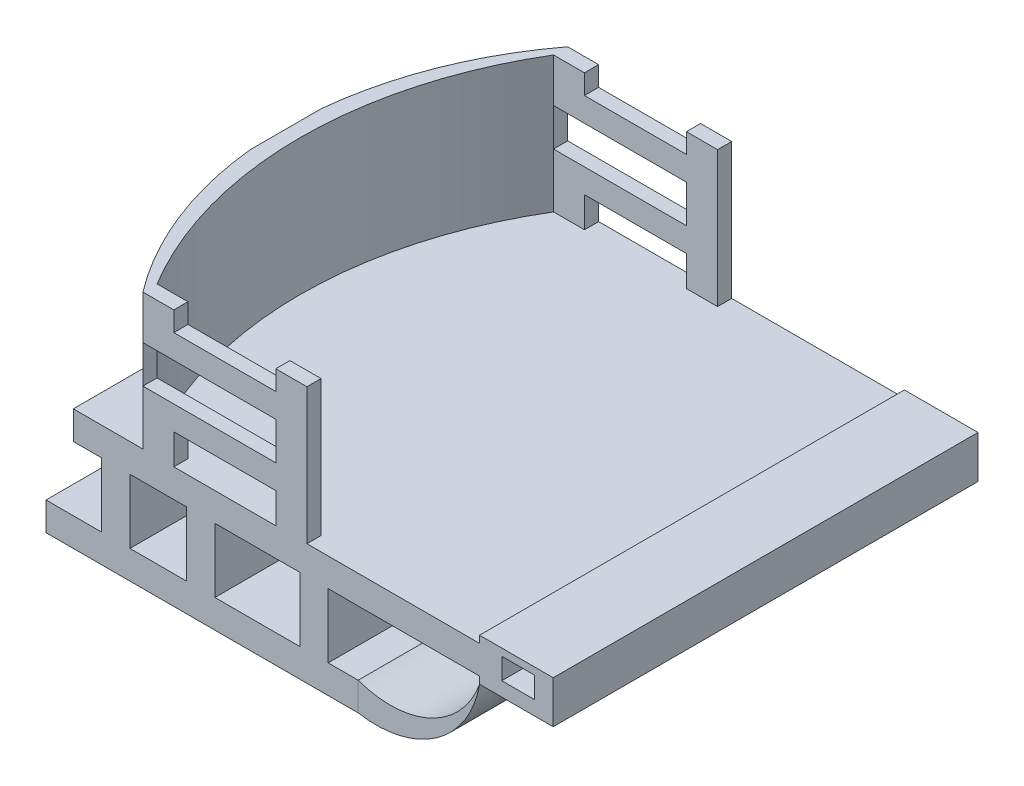
SolidWorks part; units mm, degrees
ref_plane "Front Plane" through (0, 0, 0) normal (0, 0, 1) x (1, 0, 0)
ref_plane "Top Plane" through (0, 0, 0) normal (0, 1, 0) x (1, 0, 0)
ref_plane "Right Plane" through (0, 0, 0) normal (1, 0, 0) x (0, 0, -1)
sketch "Sketch1" plane through (0, 0, 0) normal (0, 0, 1) x (1, 0, 0)
  line L1 (-50.5, 7.5) -> (99.5, 7.5)
  line L2 (-50.5, 7.5) -> (-50.5, -2.5)
  line L3 (-50.5, -2.5) -> (99.5, -2.5)
  line L4 (99.5, 7.5) -> (99.5, -2.5)
  line L5 (-40.5, -2.5) -> (-30.5, -2.5)
  line L6 (-40.5, -2.5) -> (-40.5, -27.5)
  line L7 (-40.5, -27.5) -> (-30.5, -27.5)
  line L8 (-30.5, -2.5) -> (-30.5, -27.5)
  line L9 (-10.5, -2.5) -> (-0.5, -2.5)
  line L10 (-10.5, -2.5) -> (-10.5, -27.5)
  line L11 (-10.5, -27.5) -> (-0.5, -27.5)
  line L12 (-0.5, -2.5) -> (-0.5, -27.5)
  line L13 (29.5, -2.5) -> (39.5, -2.5)
  line L14 (29.5, -2.5) -> (29.5, -27.5)
  line L15 (29.5, -27.5) -> (39.5, -27.5)
  line L16 (39.5, -2.5) -> (39.5, -27.5)
  line L17 (-25.9174, 7.5) -> (-15, 7.5)
  line L18 (-25.9174, 7.5) -> (-25.9174, 55.5)
  line L19 (-25.9174, 55.5) -> (-15, 55.5)
  line L20 (-15, 7.5) -> (-15, 55.5)
  line L21 (21, 7.5) -> (32, 7.5)
  line L22 (21, 7.5) -> (21, 55.5)
  line L23 (21, 55.5) -> (32, 55.5)
  line L24 (32, 7.5) -> (32, 55.5)
  line L25 (-40.5, -27.5) -> (-71.5, -27.5)
  line L26 (-40.5, -27.5) -> (-40.5, -32.5)
  line L27 (-40.5, -32.5) -> (-71.5, -32.5)
  line L28 (-71.5, -27.5) -> (-71.5, -32.5)
  line L29 (-40.5, -27.5) -> (73.5, -27.5)
  line L30 (-40.5, -27.5) -> (-40.5, -32.5)
  line L31 (-40.5, -32.5) -> (73.5, -32.5)
  line L32 (73.5, -27.5) -> (73.5, -32.5)
  line L33 (92.9617, -5) -> (118.9617, -5)
  line L34 (92.9617, -5) -> (92.9617, 10)
  line L35 (92.9617, 10) -> (118.9617, 10)
  line L36 (118.9617, -5) -> (118.9617, 10)
  dimension "D1" = 10
  dimension "D2" = 150
  dimension "D3" = 25
  dimension "D4" = 25
  dimension "D5" = 25
  dimension "D6" = 10
  dimension "D7" = 10
  dimension "D8" = 10
  dimension "D9" = 10
  dimension "D10" = 20
  dimension "D11" = 30
  dimension "D12" = 11
  dimension "D13" = 5
  dimension "D14" = 7
  dimension "D15" = 7
  dimension "D16" = 15
extrude "Boss-Extrude4" add sketch "Sketch1" along normal blind 150 contours L33 L36 L35 L34 L1 L4 L3 | L16 L3 L14 L15 | L12 L3 L10 L11 | L24 L23 L22 L21 | L18 L19 L20 L17 | L6 L5 L8 L7
sketch "Sketch4" plane through (0, 0, 150) normal (0, 0, 1) x (1, 0, 0)
  line L1 (-60.1333, -25.1927) -> (74.4428, -25.1927)
  line L2 (-60.1333, -25.1927) -> (-60.1333, -35.1927)
  line L3 (-60.1333, -35.1927) -> (74.4428, -35.1927)
  line L4 (74.4428, -25.1927) -> (74.4428, -35.1927)
  dimension "D1" = 10
extrude "Boss-Extrude5" add sketch "Sketch4" against normal blind 150
sketch "Sketch6" plane through (0, 0, 150) normal (0, 0, 1) x (1, 0, 0)
  line L1 (100.8107, 7.5) -> (112.4268, 7.5)
  line L2 (100.8107, 7.5) -> (100.8107, 0)
  line L3 (100.8107, 0) -> (112.4268, 0)
  line L4 (112.4268, 7.5) -> (112.4268, 0)
extrude "Cut-Extrude2" cut sketch "Sketch6" against normal blind 150
sketch "Sketch9" plane through (0, 0, 150) normal (0, 0, 1) x (1, 0, 0)
  line L0 (74.4428, -25.1927) -> (39.5, -25.1927) construction
  line L1 (50.0965, -25.1927) -> (74.4428, -25.1927)
  line L2 (50.0965, -25.1927) -> (50.0965, -35.1927)
  line L3 (50.0965, -35.1927) -> (74.4428, -35.1927)
  line L4 (74.4428, -25.1927) -> (74.4428, -35.1927)
  line L5 (-60.1333, -35.1927) -> (74.4428, -35.1927) construction
extrude "Cut-Extrude3" cut sketch "Sketch9" against normal blind 150
sketch "Sketch10" plane through (0, 0, 150) normal (0, 0, 1) x (1, 0, 0)
  line L24 (50.0965, -35.1927) -> (50.0965, -25.1927)
  line L25 (50.0965, -25.1927) -> (39.5, -25.1927)
  line L26 (39.5, -25.1927) -> (39.5, -2.5)
  line L27 (39.5, -2.5) -> (92.9617, -2.5)
  line L28 (92.9617, -2.5) -> (92.9617, -5)
  line L29 (92.9617, -5) -> (118.9617, -5)
  line L30 (118.9617, -5) -> (118.9617, 10)
  line L31 (118.9617, 10) -> (92.9617, 10)
  line L32 (92.9617, 10) -> (92.9617, 7.5)
  line L33 (92.9617, 7.5) -> (32, 7.5)
  line L34 (32, 7.5) -> (32, 55.5)
  line L35 (32, 55.5) -> (21, 55.5)
  line L36 (21, 55.5) -> (21, 7.5)
  line L37 (21, 7.5) -> (-15, 7.5)
  line L38 (-15, 7.5) -> (-15, 55.5)
  line L39 (-15, 55.5) -> (-25.9174, 55.5)
  line L40 (-25.9174, 55.5) -> (-25.9174, 7.5)
  line L41 (-25.9174, 7.5) -> (-50.5, 7.5)
  line L42 (-50.5, 7.5) -> (-50.5, -2.5)
  line L43 (-50.5, -2.5) -> (-40.5, -2.5)
  line L44 (-40.5, -2.5) -> (-40.5, -25.1927)
  line L45 (-40.5, -25.1927) -> (-60.1333, -25.1927)
  line L46 (-60.1333, -25.1927) -> (-60.1333, -35.1927)
  line L47 (-60.1333, -35.1927) -> (50.0965, -35.1927)
  line L49 (50.0965, -35.1927) -> (50.0965, -25.1927)
  arc A0 (50.0965, -25.1927) -> (92.9617, -5) centre (61.4327, 6.3362) ccw
  arc A1 (50.0965, -35.1927) -> (92.9617, -5) centre (56.4327, 1.3362) ccw
  dimension "D1" = 0
extrude "Boss-Extrude8" add sketch "Sketch10" against normal blind 150 separate body
sketch "Sketch11" plane through (32, 0, 0) normal (1, 0, 0) x (0, 0, -1)
  line L0 (-150, 55.5) -> (0, 55.5) construction
  line L1 (-145, 55.5) -> (-5, 55.5)
  line L6 (-145, 55.5) -> (-145, 7.5)
  line L7 (-150, 7.5) -> (0, 7.5) construction
  line L8 (-145, 7.5) -> (-5, 7.5)
  line L9 (-5, 7.5) -> (-5, 55.5)
  dimension "D1" = 5
  dimension "D2" = 5
extrude "Cut-Extrude5" cut sketch "Sketch11" against normal blind 150
sketch "Sketch12" plane through (0, 0, 150) normal (0, 0, 1) x (1, 0, 0)
  line L0 (-25.9174, 7.5) -> (-25.9174, 55.5) construction
  line L1 (-25.9174, 48.554) -> (32, 48.554)
  line L2 (-25.9174, 48.554) -> (-25.9174, 40.0545)
  line L3 (-25.9174, 40.0545) -> (32, 40.0545)
  line L4 (32, 48.554) -> (32, 40.0545)
  line L5 (32, 7.5) -> (32, 55.5) construction
  line L7 (-25.9174, 26.7384) -> (32, 26.7384)
  line L8 (-25.9174, 26.7384) -> (-25.9174, 18.2389)
  line L9 (-25.9174, 18.2389) -> (32, 18.2389)
  line L10 (32, 26.7384) -> (32, 18.2389)
extrude "Boss-Extrude9" add sketch "Sketch12" against normal blind 150
sketch "Sketch13" plane through (32, 0, 0) normal (1, 0, 0) x (0, 0, -1)
  line L1 (-145, 48.554) -> (-5, 48.554)
  line L2 (-145, 48.554) -> (-145, 18.2389)
  line L3 (-145, 18.2389) -> (-5, 18.2389)
  line L4 (-5, 48.554) -> (-5, 18.2389)
extrude "Cut-Extrude6" cut sketch "Sketch13" against normal blind 150
sketch "Sketch16" plane through (0, 7.5, 0) normal (0, 1, 0) x (1, 0, 0)
  line L0 (-25.9174, -145) -> (-15, -145) construction
  line L21 (32, -150) -> (92.9617, -150)
  line L22 (92.9617, -150) -> (92.9617, 0)
  line L23 (92.9617, 0) -> (32, 0)
  line L24 (32, 0) -> (32, -5)
  line L25 (32, -5) -> (21, -5)
  line L26 (21, -5) -> (21, 0)
  line L27 (21, 0) -> (-15, 0)
  line L28 (-15, 0) -> (-15, -5)
  line L29 (-15, -5) -> (-25.9174, -5)
  line L30 (-25.9174, -5) -> (-25.9174, 0)
  line L31 (-25.9174, 0) -> (-50.5, 0)
  line L32 (-50.5, 0) -> (-50.5, -150)
  line L33 (-50.5, -150) -> (-25.9174, -150)
  line L34 (-25.9174, -150) -> (-25.9174, -145)
  line L35 (-25.9174, -145) -> (-15, -145)
  line L36 (-15, -145) -> (-15, -150)
  line L37 (-15, -150) -> (21, -150)
  line L38 (21, -150) -> (21, -145)
  line L39 (21, -145) -> (32, -145)
  line L40 (32, -145) -> (32, -150)
  line L41 (32, -150) -> (92.9617, -150)
  line L42 (92.9617, -150) -> (92.9617, 0)
  line L43 (92.9617, 0) -> (32, 0)
  line L44 (32, 0) -> (32, -5)
  line L45 (32, -5) -> (21, -5)
  line L46 (21, -5) -> (21, 0)
  line L47 (21, 0) -> (-15, 0)
  line L48 (-15, 0) -> (-15, -5)
  line L49 (-15, -5) -> (-25.9174, -5)
  line L55 (-25.9174, -145) -> (-15, -145)
  line L56 (-15, -145) -> (-15, -150)
  line L57 (-15, -150) -> (21, -150)
  line L58 (21, -150) -> (21, -145)
  line L59 (21, -145) -> (32, -145)
  line L60 (32, -145) -> (32, -150)
  arc A0 (-25.9174, 0) -> (-25.9174, -150) centre (72.9875, -75) ccw
  arc A1 (-25.9174, -145) -> (-25.9174, -5) centre (90.1931, -75) cw
  line M30 (-25.9174, -5) -> (-25.9174, 0)
  line M32 (-50.5, 0) -> (-50.5, -150)
  line M34 (-25.9174, -150) -> (-25.9174, -145)
  dimension "D1" = 0
extrude "Boss-Extrude10" add sketch "Sketch16" along normal blind 48 contours A1 A0 M34 M30 M32
sketch "Sketch17" plane through (0, 0, 150) normal (0, 0, 1) x (1, 0, 0)
  line L0 (-25.9174, 7.5) -> (-25.9174, 55.5) construction
  line L1 (-15, 40.0545) -> (-25.9174, 40.0545)
  line L2 (-15, 40.0545) -> (-15, 26.7384)
  line L3 (-15, 26.7384) -> (-25.9174, 26.7384)
  line L4 (-25.9174, 40.0545) -> (-25.9174, 26.7384)
extrude "Cut-Extrude7" cut sketch "Sketch17" against normal blind 150
